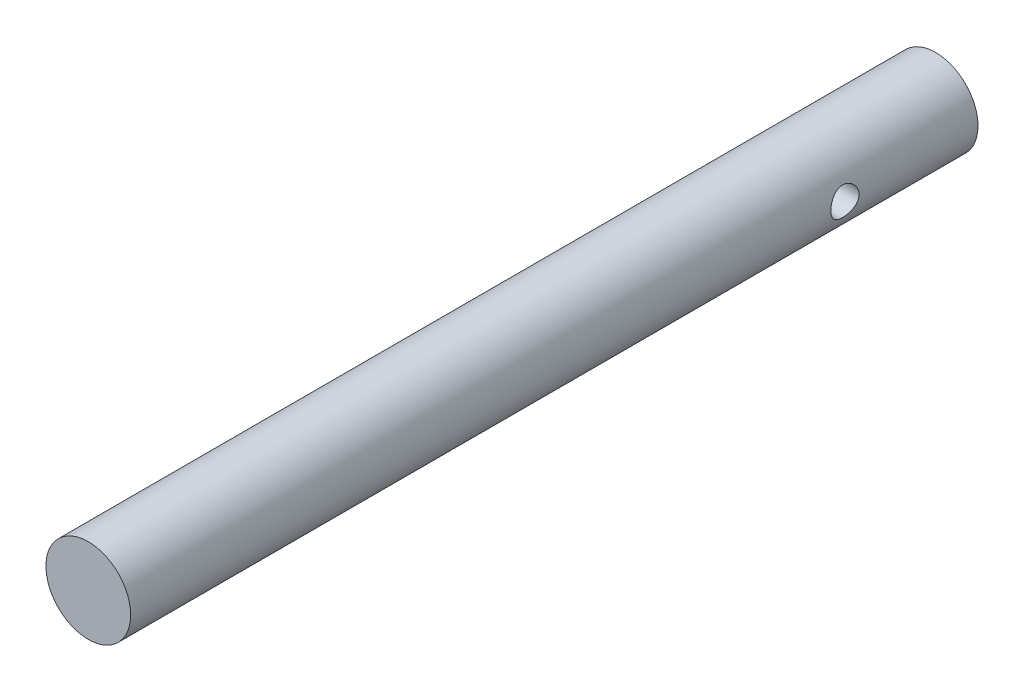
SolidWorks part; units mm, degrees
ref_plane "Front Plane" through (0, 0, 0) normal (0, 0, 1) x (1, 0, 0)
ref_plane "Top Plane" through (0, 0, 0) normal (0, 1, 0) x (1, 0, 0)
ref_plane "Right Plane" through (0, 0, 0) normal (1, 0, 0) x (0, 0, -1)
sketch "Sketch1" plane through (0, 0, 0) normal (0, 0, 1) x (1, 0, 0)
  circle A0 centre (0, 0) radius 3
  dimension "D1" = 6
extrude "Boss-Extrude1" add sketch "Sketch1" along normal blind 60
sketch "Sketch2" plane through (0, 0, 0) normal (1, 0, 0) x (0, 0, -1)
  line L1 (0, -3) -> (0, 3) construction
  circle A0 centre (-9.42, 0) radius 1
  dimension "D1" = 2
  dimension "D2" = 9.42
extrude "Cut-Extrude1" cut sketch "Sketch2" against normal through all both and the other way through all contours A0
